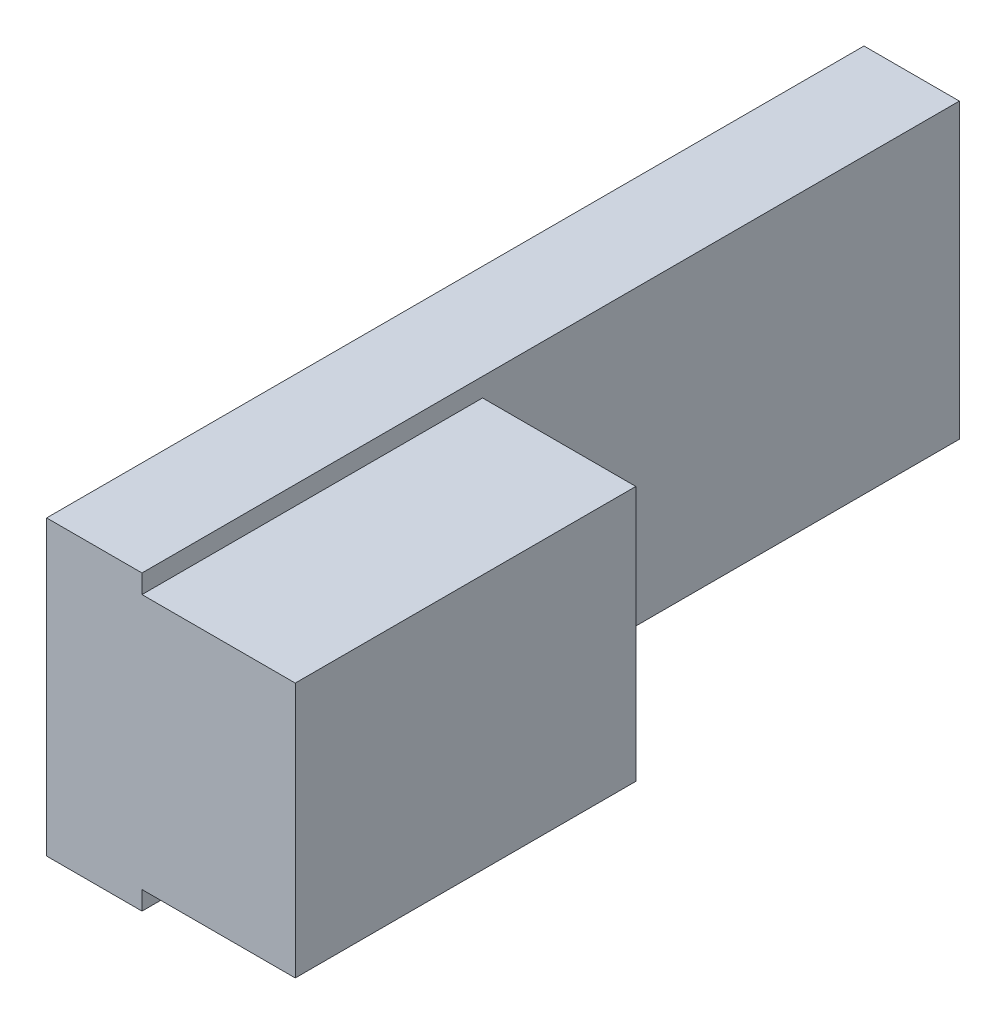
SolidWorks part; units mm, degrees
ref_plane "前视基准面" through (0, 0, 0) normal (0, 0, 1) x (1, 0, 0)
ref_plane "上视基准面" through (0, 0, 0) normal (0, 1, 0) x (1, 0, 0)
ref_plane "右视基准面" through (0, 0, 0) normal (1, 0, 0) x (0, 0, -1)
other "Configuration Table"
ref_plane "基准面1" through (0, 0, 0) normal (-1, 0, 0) x (0, -1, 0)
sketch "草图1" plane through (0, 0, 0) normal (-1, 0, 0) x (0, -1, 0)
  line L0 (-8.6, -24) -> (8.6, -24)
  line L1 (8.6, -24) -> (8.6, 24)
  line L2 (8.6, 24) -> (-8.6, 24)
  line L3 (-8.6, 24) -> (-8.6, -24)
  dimension "D1" = 17.2
  dimension "D2" = 48
extrude "凸台-拉伸1" add sketch "草图1" against normal blind 5.6
sketch "草图2" plane through (5.6, 0, 0) normal (1, 0, 0) x (0, 0, -1)
  line L0 (-4, 7.5) -> (-4, -7.5)
  line L1 (-4, -7.5) -> (-24, -7.5)
  line L2 (-24, -7.5) -> (-24, 7.5)
  line L3 (-24, 7.5) -> (-4, 7.5)
  line L4 (-24, 8.6) -> (24, 8.6) construction
  dimension "D1" = 28
  dimension "D2" = 48
  dimension "D3" = 1.1
  dimension "D4" = 16.1
extrude "凸台-拉伸2" add sketch "草图2" along normal blind 9
